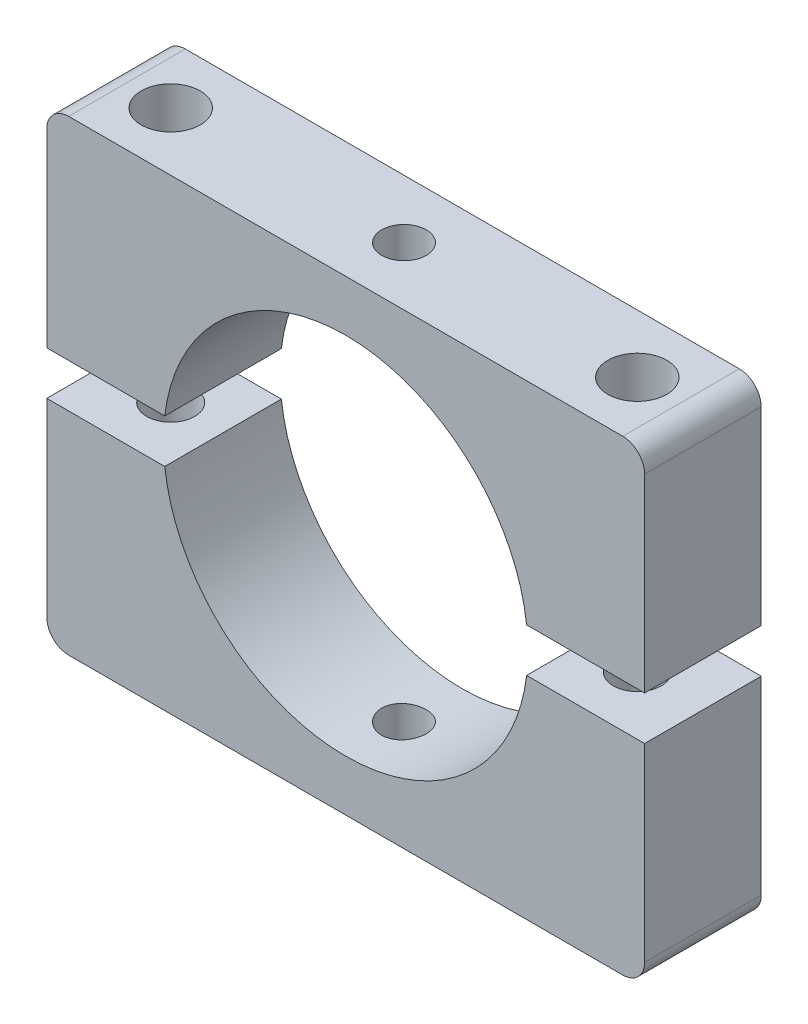
SolidWorks part; units mm, degrees
material "6061 合金"
ref_plane "前视基准面" through (0, 0, 0) normal (0, 0, 1) x (1, 0, 0)
ref_plane "上视基准面" through (0, 0, 0) normal (0, 1, 0) x (1, 0, 0)
ref_plane "右视基准面" through (0, 0, 0) normal (1, 0, 0) x (0, 0, -1)
other "Configuration Table"
sketch "草图1" plane through (0, 0, 0) normal (0, 0, 1) x (1, 0, 0)
  line L1 (-20.5, -16) -> (20.5, -16)
  line L2 (-20.5, -16) -> (-20.5, 16)
  line L3 (-20.5, 16) -> (20.5, 16)
  line L4 (20.5, -16) -> (20.5, 16)
  line L5 (-20.5, -16) -> (20.5, 16) construction
  line L6 (-20.5, 16) -> (20.5, -16) construction
  circle A0 centre (0, 0) radius 12.5
  point P0 (0, 0)
  dimension "D1" = 25
  dimension "D2" = 8
  dimension "D3" = 3.5
extrude "凸台-拉伸1" add sketch "草图1" along normal mid plane 8
fillet "圆角1" radius 1.5 4 edges at (20.5, -16, 0) (-20.5, -16, 0) (-20.5, 16, 0) (20.5, 16, 0)
sketch "草图2" plane through (0, 0, 4) normal (0, 0, 1) x (1, 0, 0)
  line L1 (-25.5, -1.5) -> (25.5, -1.5)
  line L2 (-25.5, -1.5) -> (-25.5, 1.5)
  line L3 (-25.5, 1.5) -> (25.5, 1.5)
  line L4 (25.5, -1.5) -> (25.5, 1.5)
  line L5 (-25.5, -1.5) -> (25.5, 1.5) construction
  line L6 (-25.5, 1.5) -> (25.5, -1.5) construction
  point P0 (0, 0)
  dimension "D1" = 3
  dimension "D2" = 51
extrude "切除-拉伸2" cut sketch "草图2" against normal mid plane 48
sketch "草图3" plane through (0, 16, 0) normal (0, 1, 0) x (1, 0, 0)
  line L0 (-16, 0) -> (16, 0) construction
  line L1 (20.5, 4) -> (20.5, -4) construction
  circle A0 centre (16, 0) radius 2.025
  circle A1 centre (-16, 0) radius 2.025
  point P4 (0, 0)
  dimension "D2" = 4.05
  dimension "D1" = 4.5
extrude "切除-拉伸3" cut sketch "草图3" against normal up to surface (14.5 mm away) up to face at (-16.4548, 1.5, 0)
hole_wizard "M4 螺纹孔1" positions "草图4" profile "草图5" tap size "M4" standard "GB" end condition through all
sketch "草图4" plane through (0, -1.5, 0) normal (0, 1, 0) x (1, 0, 0)
  point P0 (-16, 0)
  point P3 (16, 0)
sketch "草图5" plane through (-16, -1.5, 0) normal (1, 0, 0) x (0, 0, 1)
  line L0 (0, 0) -> (0, 14.5)
  line L1 (0, 14.5) -> (1.65, 14.5)
  line L2 (1.65, 14.5) -> (1.65, 0)
  line L5 (1.65, 0) -> (0, 0)
  line L11 (0, -6.35) -> (0, 107.95) construction
  dimension "通孔螺纹孔钻头直径" = 3.3
  dimension "通孔螺纹孔钻头深度" = 14.5
cosmetic thread "孔螺蚊线1" parameters "D2"=4
cosmetic thread "孔螺蚊线2" parameters "D2"=4
sketch "草图6" plane through (0, 16, 0) normal (0, 1, 0) x (1, 0, 0)
  circle A0 centre (0, 0) radius 1.525
  dimension "D1" = 3.05
extrude "切除-拉伸4" cut sketch "草图6" against normal up to surface (32 mm away)
